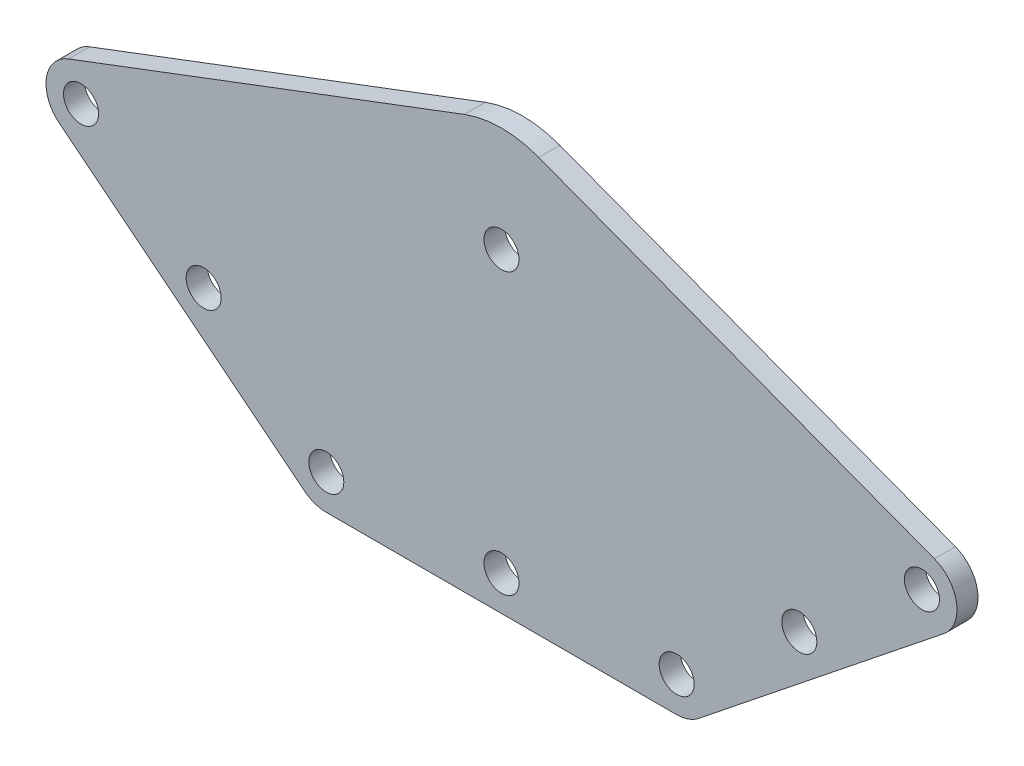
SolidWorks part; units mm, degrees
ref_plane "Front Plane" through (0, 0, 0) normal (0, 0, 1) x (1, 0, 0)
ref_plane "Top Plane" through (0, 0, 0) normal (0, 1, 0) x (1, 0, 0)
ref_plane "Right Plane" through (0, 0, 0) normal (1, 0, 0) x (0, 0, -1)
sketch "Sketch2" plane through (0, 0, 0) normal (0, 0, 1) x (1, 0, 0)
  line L0 (0, 0) -> (30, 0) construction
  line L1 (0, 0) -> (-30, 0) construction
  line L2 (0, 0) -> (0, 40) construction
  line L3 (0, 0) -> (-60, 27.9785) construction
  line L4 (0, 0) -> (60, 27.9785) construction
  line L5 (-61.7702, 32.6546) -> (-5.3107, 54.0284)
  line L6 (-63.122, 24.0729) -> (-28.122, -3.9055)
  line L7 (0, -5) -> (-25, -5)
  line L8 (0, -5) -> (25, -5)
  line L9 (28.122, -3.9055) -> (63.122, 24.0729)
  line L10 (5.3107, 54.0284) -> (61.7702, 32.6546)
  line L11 (-60, 27.9785) -> (-25, 0) construction
  line L12 (-60, 27.9785) -> (0, 40) construction
  line L13 (60, 27.9785) -> (25, 0) construction
  circle A0 centre (-25, 0) radius 5 construction
  circle A1 centre (25, 0) radius 5 construction
  circle A2 centre (0, 40) radius 15 construction
  circle A3 centre (-60, 27.9785) radius 5 construction
  circle A4 centre (60, 27.9785) radius 5 construction
  circle A5 centre (0, 0) radius 5 construction
  arc A6 (-63.122, 24.0729) -> (-61.7702, 32.6546) centre (-60, 27.9785) cw
  arc A7 (-5.3107, 54.0284) -> (5.3107, 54.0284) centre (0, 40) cw
  arc A8 (-28.122, -3.9055) -> (-25, -5) centre (-25, 0) ccw
  arc A9 (25, -5) -> (28.122, -3.9055) centre (25, 0) ccw
  arc A10 (63.122, 24.0729) -> (61.7702, 32.6546) centre (60, 27.9785) ccw
  circle A11 centre (-60, 27.9785) radius 2.5
  circle A12 centre (0, 40) radius 2.5
  circle A13 centre (60, 27.9785) radius 2.5
  circle A14 centre (25, 0) radius 2.5
  circle A15 centre (0, 0) radius 2.5
  circle A16 centre (-25, 0) radius 2.5
  circle A17 centre (-42.5, 13.9892) radius 5 construction
  circle A18 centre (42.5, 13.9892) radius 5 construction
  circle A19 centre (-42.5, 13.9892) radius 2.5
  circle A20 centre (42.5, 13.9892) radius 2.5
  point P3 (-25, 0)
  point P5 (25, 0)
  dimension "D5" = 30
  dimension "D10" = 10
  dimension "D11" = 10
  dimension "D12" = 10
  dimension "D13" = 5
  dimension "D1" = 60
  dimension "D2" = 5
  dimension "D3" = 5
  dimension "D4" = 40
  dimension "D6" = 25
  dimension "D7" = 60
  dimension "D8" = 25
  dimension "D9" = 60
extrude "Boss-Extrude1" add sketch "Sketch2" along normal blind 3
